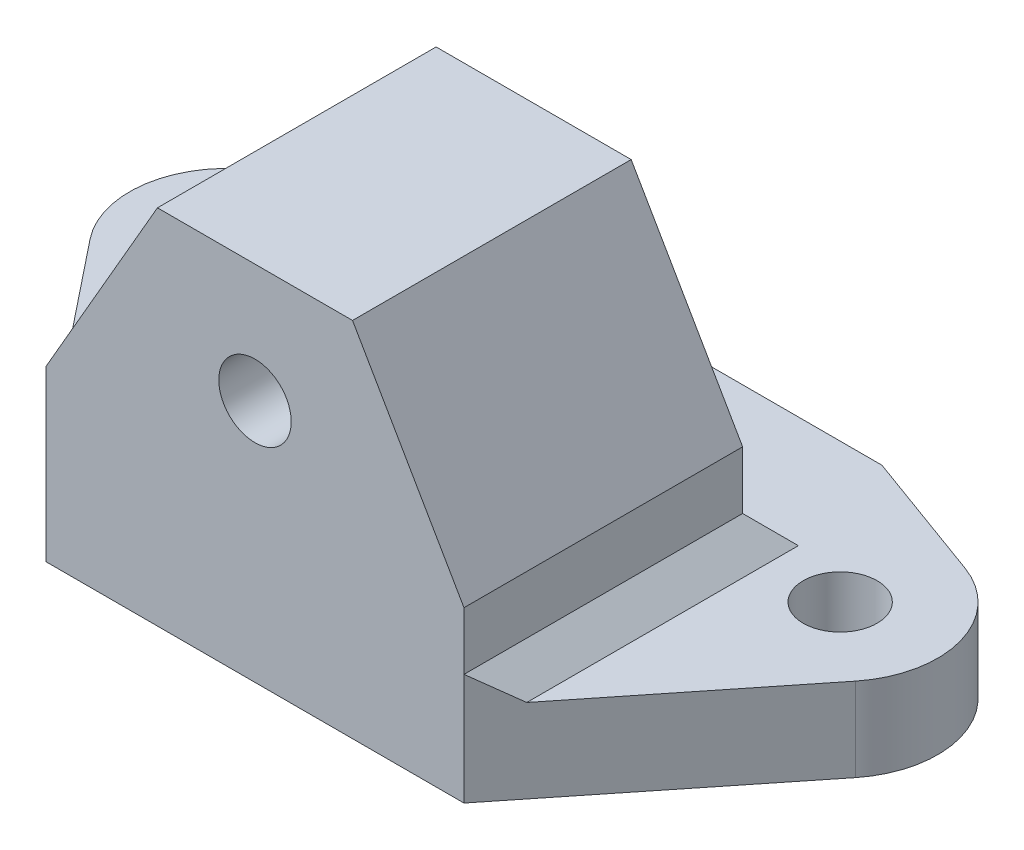
SolidWorks part; units mm, degrees
ref_plane "Front Plane" through (0, 0, 0) normal (0, 0, 1) x (1, 0, 0)
ref_plane "Top Plane" through (0, 0, 0) normal (0, 1, 0) x (1, 0, 0)
ref_plane "Right Plane" through (0, 0, 0) normal (1, 0, 0) x (0, 0, -1)
sketch "Sketch1" plane through (0, 0, 0) normal (0, 0, 1) x (1, 0, 0)
  line L1 (-15, 13) -> (15, 13)
  line L2 (-15, 13) -> (-15, -13)
  line L3 (-15, -13) -> (15, -13)
  line L4 (15, 13) -> (15, -13)
  line L5 (-15, 13) -> (15, -13) construction
  line L6 (-15, -13) -> (15, 13) construction
  point P0 (0, 0)
  dimension "D1" = 26
  dimension "D2" = 30
extrude "Boss-Extrude1" add sketch "Sketch1" along normal blind 30
sketch "Sketch2" plane through (0, 0, 0) normal (0, 0, 1) x (1, 0, 0)
  line L2 (0, -14.3) -> (0, 14.3) construction
  line L3 (16.5, 0) -> (-16.5, 0) construction
  circle A0 centre (0, 4.5) radius 5.25
  dimension "D1" = 10.5
  dimension "D2" = 4.5
extrude "Cut-Extrude1" cut sketch "Sketch2" along normal blind 15
sketch "Sketch3" plane through (0, 0, 0) normal (0, 0, 1) x (1, 0, 0)
  line L0 (16.5, 0) -> (-16.5, 0) construction
  line L1 (0, -14.3) -> (0, 14.3) construction
  circle A0 centre (0, 4.5) radius 2.6
  dimension "D1" = 5.2
  dimension "D2" = 4.5
extrude "Cut-Extrude2" cut sketch "Sketch3" along normal up to next
sketch "Sketch4" plane through (0, -13, 0) normal (0, -1, 0) x (1, 0, 0)
  line L0 (-22, 10) -> (34.0128, 10) construction
  line L1 (14.3, 0) -> (-14.3, 0) construction
  line L2 (0, -1.0234) -> (0, 38.56) construction
  line L3 (0, -14.3) -> (0, 14.3) construction
  line L4 (-15, 30) -> (-27.4722, 14.3653)
  line L5 (-15, 0) -> (-24.396, 3.4228)
  line L6 (-15, 30) -> (-15, 0) construction
  line L7 (15, 0) -> (24.396, 3.4228)
  line L8 (15, 30) -> (27.4722, 14.3653)
  line L9 (-15, 30) -> (-15, 0)
  line L10 (15, 30) -> (15, 0)
  arc A0 (-27.4722, 14.3653) -> (-24.396, 3.4228) centre (-22, 10) ccw
  circle A1 centre (-22, 10) radius 2.65
  circle A2 centre (22, 10) radius 2.65
  arc A3 (27.4722, 14.3653) -> (24.396, 3.4228) centre (22, 10) cw
  dimension "D3" = 7
  dimension "D4" = 5.3
  dimension "D1" = 10
  dimension "D2" = 22
extrude "Boss-Extrude2" add sketch "Sketch4" against normal blind 6
chamfer "Chamfer1" distance 8 angle 60 2 edges at (-15, 13, 15) (15, 13, 15)
sketch "Sketch5" plane through (0, 0, 0) normal (1, 0, 0) x (0, 0, -1)
  line L0 (-30, 13) -> (0, 13) construction
  line L1 (-10, 13) -> (0, 13)
  line L2 (-10, 13) -> (-10, -7)
  line L3 (-10, -7) -> (0, -7)
  line L4 (0, 13) -> (0, -7)
  line L5 (0, 14.3) -> (0, -14.3) construction
  line L7 (0, -7) -> (-3.4228, -7) construction
  dimension "D1" = 10
extrude "Cut-Extrude3" cut sketch "Sketch5" against normal mid plane 40
chamfer "Chamfer2" distance 2 angle 45 3 edges at (0, -7, 10)
